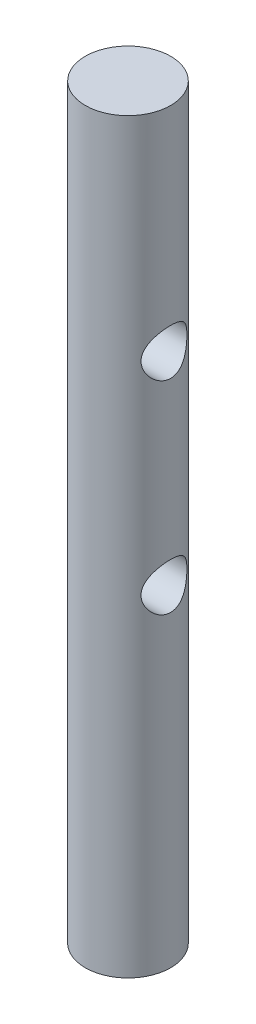
SolidWorks part; units mm, degrees
ref_plane "Front Plane" through (0, 0, 0) normal (0, 0, 1) x (1, 0, 0)
ref_plane "Top Plane" through (0, 0, 0) normal (0, 1, 0) x (1, 0, 0)
ref_plane "Right Plane" through (0, 0, 0) normal (1, 0, 0) x (0, 0, -1)
sketch "Sketch1" plane through (0, 0, 0) normal (0, 1, 0) x (1, 0, 0)
  circle A0 centre (0, 0) radius 4
  dimension "D1" = 8
extrude "Boss-Extrude1" add sketch "Sketch1" along normal blind 70
ref_plane "Plane1" through (4, 0, 0) normal (1, 0, 0) x (0, 0, -1)
sketch "Sketch2" plane through (4, 0, 0) normal (1, 0, 0) x (0, 0, -1)
  line L0 (4, 0) -> (4, 70) construction
  circle A0 centre (0, 31) radius 1.5
  circle A1 centre (0, 50) radius 1.5
  dimension "D1" = 3
  dimension "D2" = 3
  dimension "D3" = 4
  dimension "D4" = 4
  dimension "D5" = 31
  dimension "D6" = 50
hole_wizard "M4 Clearance Hole1" positions "Sketch3" profile "Sketch4" hole size "M4" standard "ANSI Metric" end condition through all
sketch "Sketch3" plane through (4, 0, 0) normal (1, 0, 0) x (0, 0, -1)
  point P0 (0, 50)
  point P3 (0, 31)
sketch "Sketch4" plane through (4, 50, 0) normal (0, 1, 0) x (0, 0, -1)
  line L0 (0, 0) -> (0, 8)
  line L1 (0, 8) -> (2.15, 8)
  line L2 (2.15, 8) -> (2.15, 0)
  line L5 (2.15, 0) -> (0, 0)
  line L11 (0, -6.35) -> (0, 107.95) construction
  dimension "Thru Hole Dia." = 4.3
  dimension "Thru Hole Depth" = 8
